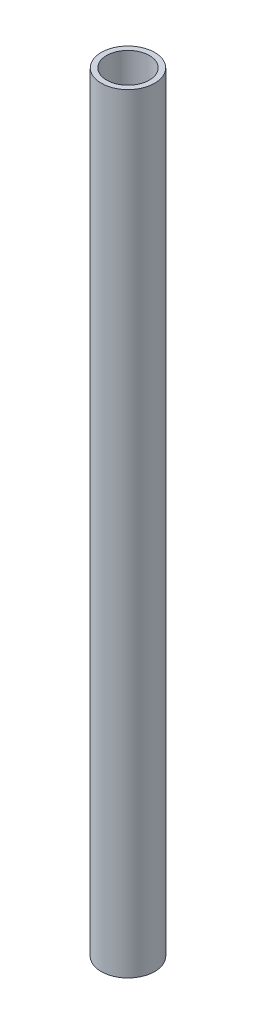
SolidWorks part; units mm, degrees
ref_plane "Front" through (0, 0, 0) normal (0, 0, 1) x (1, 0, 0)
ref_plane "Top" through (0, 0, 0) normal (0, 1, 0) x (1, 0, 0)
ref_plane "Right" through (0, 0, 0) normal (1, 0, 0) x (0, 0, -1)
sketch "Sketch1" plane through (0, 0, 0) normal (0, 1, 0) x (1, 0, 0)
  circle A0 centre (0, 0) radius 15.875
  circle A1 centre (0, 0) radius 12.7
  dimension "D1" = 31.75
  dimension "D2" = 25.4
extrude "Boss-Extrude1" add sketch "Sketch1" along normal mid plane 457.2 contours A1
